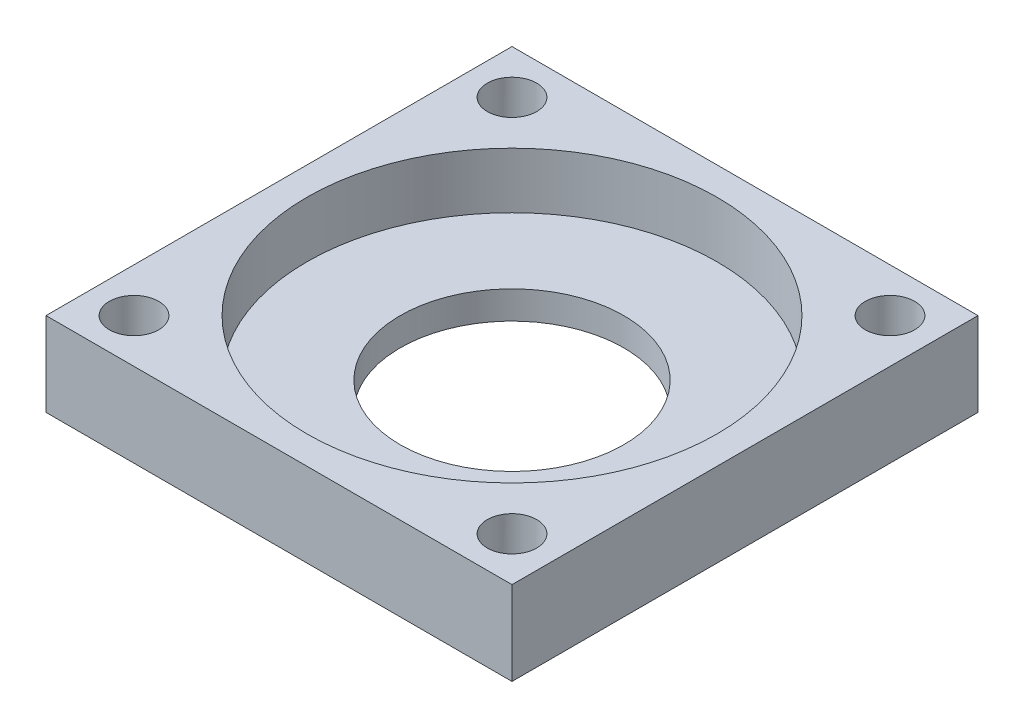
SolidWorks part; units mm, degrees
material "PLA"
ref_plane "Front Plane" through (0, 0, 0) normal (0, 0, 1) x (1, 0, 0)
ref_plane "Top Plane" through (0, 0, 0) normal (0, 1, 0) x (1, 0, 0)
ref_plane "Right Plane" through (0, 0, 0) normal (1, 0, 0) x (0, 0, -1)
sketch "Sketch1" plane through (0, 0, 0) normal (0, 1, 0) x (1, 0, 0)
  line L1 (-25, -25) -> (25, -25)
  line L2 (-25, -25) -> (-25, 25)
  line L3 (-25, 25) -> (25, 25)
  line L4 (25, -25) -> (25, 25)
  line L5 (-25, -25) -> (25, 25) construction
  line L6 (-25, 25) -> (25, -25) construction
  circle A0 centre (0, 0) radius 12
  dimension "D1" = 24
  dimension "D2" = 50
  dimension "D3" = 50
extrude "Boss-Extrude1" add sketch "Sketch1" along normal blind 3
sketch "Sketch2" plane through (0, 3, 0) normal (0, 1, 0) x (1, 0, 0)
  line L1 (-25, -25) -> (25, -25)
  line L2 (-25, -25) -> (-25, 25)
  line L3 (-25, 25) -> (25, 25)
  line L4 (25, -25) -> (25, 25)
  line L5 (-25, -25) -> (25, 25) construction
  line L6 (-25, 25) -> (25, -25) construction
  circle A0 centre (0, 0) radius 22
  dimension "D1" = 44
extrude "Boss-Extrude2" add sketch "Sketch2" along normal blind 6
sketch "Sketch3" plane through (0, 9, 0) normal (0, 1, 0) x (1, 0, 0)
  line L0 (-25, 25) -> (-15.5563, 15.5563) construction
  line L1 (0, 0) -> (0, 25) construction
  line L2 (25, 25) -> (-25, 25) construction
  line L3 (0, 0) -> (-25, 0) construction
  line L4 (-25, 25) -> (-25, -25) construction
  circle A0 centre (0, 0) radius 22 construction
  circle A1 centre (-20.2782, 20.2782) radius 2.65
  circle A2 centre (-20.2782, -20.2782) radius 2.65
  circle A3 centre (20.2782, -20.2782) radius 2.65
  circle A4 centre (20.2782, 20.2782) radius 2.65
  dimension "D1" = 5.3
extrude "Cut-Extrude1" cut sketch "Sketch3" against normal blind 30
